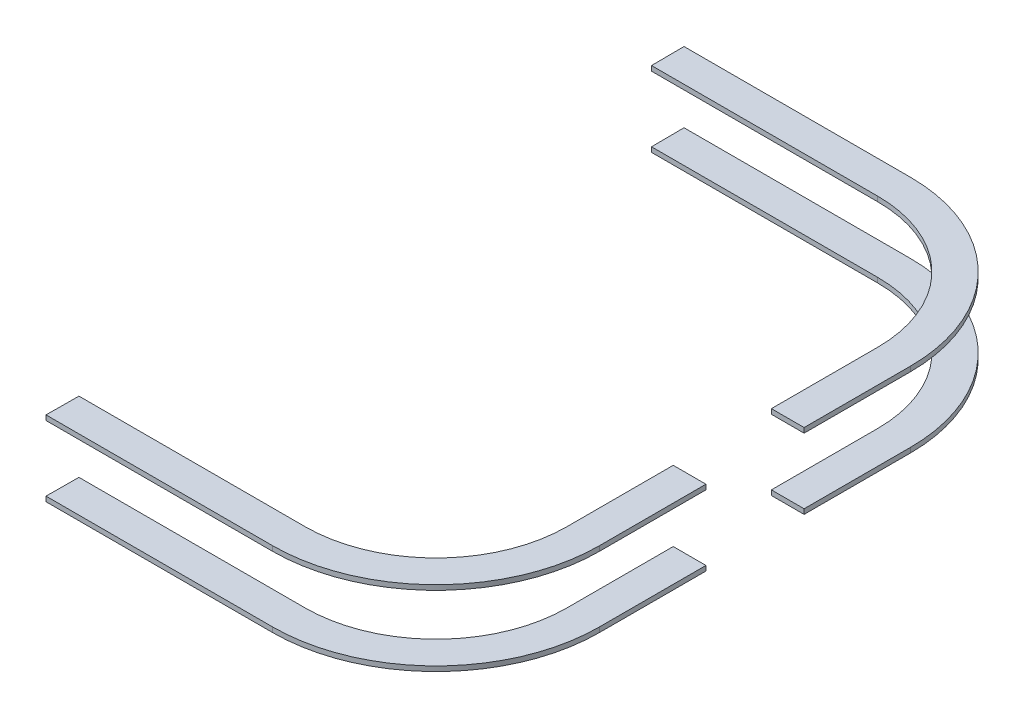
SolidWorks part; units mm, degrees
material "Alloy Steel"
ref_plane "Front Plane" through (0, 0, 0) normal (0, 0, 1) x (1, 0, 0)
ref_plane "Top Plane" through (0, 0, 0) normal (0, 1, 0) x (1, 0, 0)
ref_plane "Right Plane" through (0, 0, 0) normal (1, 0, 0) x (0, 0, -1)
sketch "Sketch1" plane through (0, 0, 0) normal (0, 1, 0) x (1, 0, 0)
  line L0 (0.0726, 9.9997) -> (100.0726, 9.9997)
  line L2 (99.9274, -9.9997) -> (-0.0726, -9.9997)
  line L3 (-0.0726, -9.9997) -> (0.0726, 9.9997)
  line L4 (218.3274, 155.0003) -> (218.3274, 95.0003)
  line L6 (238.3274, 95.0003) -> (238.3274, 155.0003)
  line L7 (238.3274, 155.0003) -> (218.3274, 155.0003)
  line L13 (-13.8003, 185.0003) -> (298.7705, 185.0003) construction
  line L38 (218.3274, 95.0003) -> (218.3274, 89.9997)
  line L39 (138.3274, 9.9997) -> (100.0726, 9.9997)
  line L40 (238.3274, 95.0003) -> (238.3274, 90.0003)
  line L41 (138.3274, -9.9997) -> (99.9274, -9.9997)
  line L52 (138.3274, 380.0003) -> (99.9274, 380.0003)
  line L53 (238.3274, 275.0003) -> (238.3274, 280.0003)
  line L54 (138.3274, 360.0008) -> (100.0726, 360.0008)
  line L55 (218.3274, 275.0003) -> (218.3274, 280.0008)
  line L56 (238.3274, 215.0003) -> (218.3274, 215.0003)
  line L57 (238.3274, 275.0003) -> (238.3274, 215.0003)
  line L58 (218.3274, 215.0003) -> (218.3274, 275.0003)
  line L59 (-0.0726, 380.0003) -> (0.0726, 360.0008)
  line L60 (99.9274, 380.0003) -> (-0.0726, 380.0003)
  line L61 (0.0726, 360.0008) -> (100.0726, 360.0008)
  arc A15 (218.3274, 89.9997) -> (138.3274, 9.9997) centre (138.3274, 89.9997) cw
  arc A16 (238.3274, 90.0003) -> (138.3274, -9.9997) centre (138.3274, 90.0003) cw
  arc A19 (238.3274, 280.0003) -> (138.3274, 380.0003) centre (138.3274, 280.0003) ccw
  arc A20 (218.3274, 280.0008) -> (138.3274, 360.0008) centre (138.3274, 280.0008) ccw
  point P3 (0, 0)
  dimension "D5" = 30
  dimension "D6" = 238.4
  dimension "D7" = 165
  dimension "D8" = 80
  dimension "D9" = 100
  dimension "D1" = 20
  dimension "D2" = 100
  dimension "D3" = 20
  dimension "D4" = 60
extrude "Boss-Extrude1" add sketch "Sketch1" along normal blind 3
pattern_linear "LPattern2" count 2 spacing 43 along (0, -1, 0) of "Boss-Extrude1"
